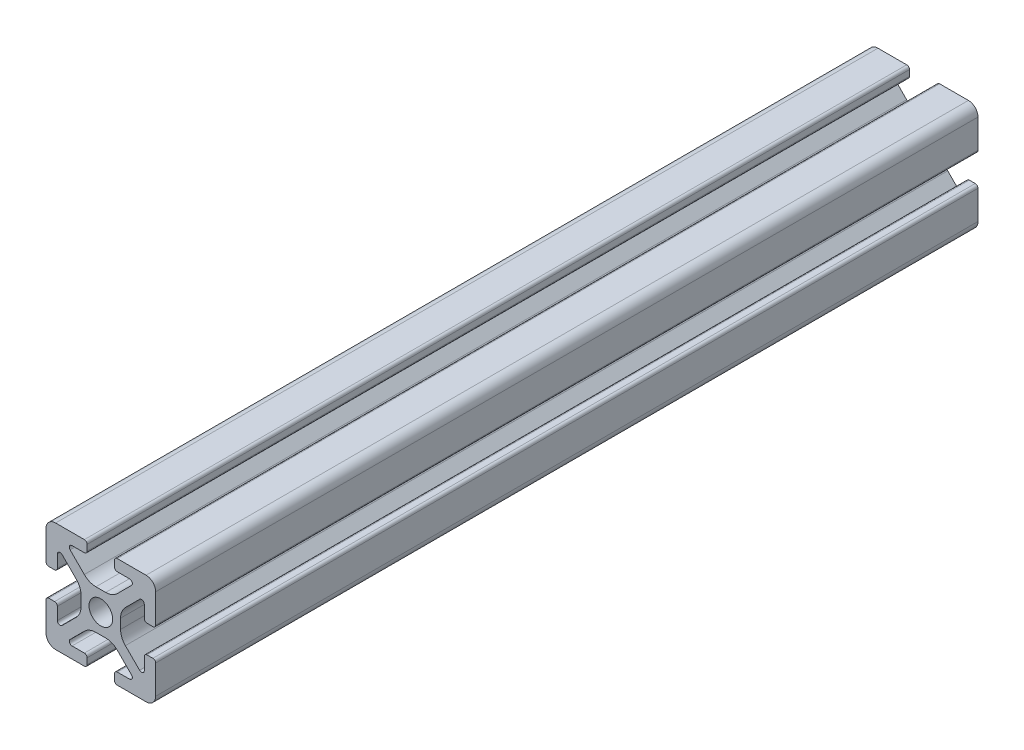
SolidWorks part; units mm, degrees
ref_plane "Front Plane" through (0, 0, 0) normal (0, 0, 1) x (1, 0, 0)
ref_plane "Top Plane" through (0, 0, 0) normal (0, 1, 0) x (1, 0, 0)
ref_plane "Right Plane" through (0, 0, 0) normal (1, 0, 0) x (0, 0, -1)
sketch "Sketch2" plane through (0, 0, 0) normal (0, 0, 1) x (1, 0, 0)
  line L0 (0, 10) -> (0, -10) construction
  line L1 (-10, 0) -> (10, 0) construction
  line L2 (2.5, -10) -> (10, -10)
  line L3 (10, -10) -> (10, -2.5)
  line L4 (2.5, -10) -> (2.5, -7.9246)
  line L5 (2.5, -7.9246) -> (6.4571, -7.9246)
  line L6 (6.4571, -7.9246) -> (2.1325, -3.6)
  line L7 (0, 0) -> (10, -10) construction
  line L8 (10, -2.5) -> (7.9246, -2.5)
  line L9 (7.9246, -2.5) -> (7.9246, -6.4571)
  line L10 (7.9246, -6.4571) -> (3.6, -2.1325)
  line L11 (5.7623, -4.2948) -> (4.2948, -5.7623) construction
  circle A0 centre (0, 0) radius 2.15
  arc A1 (5.25, -7.9246) -> (5.6036, -7.0711) centre (5.25, -7.4246) ccw construction
  point P8 (0, -3.6)
  point P16 (5.0286, -5.0286)
  dimension "Center Hole Diameter" = 4.3
  dimension "D3" = 0.5
  dimension "Rail Height" = 20
  dimension "Rail Width" = 20
  dimension "T-Slot Width" = 5
  dimension "Slot Depth" = 6.4
  dimension "Slot Inner Width" = 11.5
sketch "Sketch3" plane through (0, 0, 0) normal (1, 0, 0) x (0, 0, -1)
  line L0 (-457.2, -10) -> (457.2, -10) construction
  line L1 (-431.8, 0) -> (431.8, 0) construction
  line L2 (0, 10) -> (0, -10) construction
  line L3 (0, 10) -> (0, -10) construction
  point P6 (-431.8, 0)
  point P8 (431.8, 0)
  dimension "Length" = 914.4
  dimension "D1" = 25.4
sketch "Sketch4" plane through (0, 0, 0) normal (0, 0, 1) x (1, 0, 0)
  line L0 (3, -10) -> (8.25, -10)
  line L1 (2.5, -10) -> (10, -10) construction
  line L2 (2.5, -10) -> (2.5, -7.9246) construction
  line L3 (2.5, -7.9246) -> (6.4571, -7.9246) construction
  line L4 (2.5, -8.4246) -> (2.5, -9.5)
  line L5 (3, -7.9246) -> (5.25, -7.9246)
  line L6 (0, -3.6) -> (0.8898, -3.6)
  line L7 (6.4571, -7.9246) -> (2.1325, -3.6) construction
  line L8 (3.0112, -4.4787) -> (5.6036, -7.0711)
  line L9 (10, -10) -> (10, -2.5) construction
  line L10 (7.9246, -6.4571) -> (3.6, -2.1325) construction
  line L11 (7.9246, -2.5) -> (7.9246, -6.4571) construction
  line L12 (7.9246, -5.25) -> (7.9246, -3)
  line L13 (10, -2.5) -> (7.9246, -2.5) construction
  line L14 (8.4246, -2.5) -> (9.5, -2.5)
  line L15 (10, -3) -> (10, -8.25)
  line L16 (7.0711, -5.6036) -> (4.4787, -3.0112)
  line L17 (3.6, 0) -> (3.6, -0.8898)
  line L18 (-10, 0) -> (10, 0) construction
  line L19 (0, -3.6) -> (0, -2.15)
  line L20 (0, 10) -> (0, -10) construction
  line L21 (3.6, 0) -> (2.15, 0)
  arc A0 (2.5, -9.5) -> (3, -10) centre (3, -9.5) ccw
  arc A1 (5.25, -7.9246) -> (5.6036, -7.0711) centre (5.25, -7.4246) ccw construction
  arc A2 (2.5, -8.4246) -> (3, -7.9246) centre (3, -8.4246) cw
  arc A3 (5.25, -7.9246) -> (5.6036, -7.0711) centre (5.25, -7.4246) ccw
  arc A4 (0.8898, -3.6) -> (3.0112, -4.4787) centre (0.8898, -6.6) cw
  arc A5 (8.25, -10) -> (10, -8.25) centre (8.25, -8.25) ccw
  arc A6 (7.0711, -5.6036) -> (7.9246, -5.25) centre (7.4246, -5.25) ccw
  arc A7 (7.9246, -3) -> (8.4246, -2.5) centre (8.4246, -3) cw
  arc A8 (9.5, -2.5) -> (10, -3) centre (9.5, -3) cw
  arc A9 (4.4787, -3.0112) -> (3.6, -0.8898) centre (6.6, -0.8898) cw
  circle A10 centre (0, 0) radius 2.15 construction
  arc A11 (0, -2.15) -> (2.15, 0) centre (0, 0) ccw
  dimension "D1" = 1.75
  dimension "D2" = 3
extrude "Boss-Extrude1" add sketch "Sketch4" along normal mid plane 150
mirror "Mirror1" about plane through (0, 0, 0) normal (1, 0, 0) of bodies 134
mirror "Mirror2" about plane through (0, 0, 0) normal (0, 1, 0) of bodies 135
equation "\"D3@Sketch2\"=\"T-Slot Width@Sketch2\"*0.1"
equation "\"D1@Sketch4\"=\"D3@Sketch2\"*3.5"
equation "\"D2@Sketch4\"=\"D3@Sketch2\"*6"
equation "\"D1@Boss-Extrude1\"=\"Length@Sketch3\""
